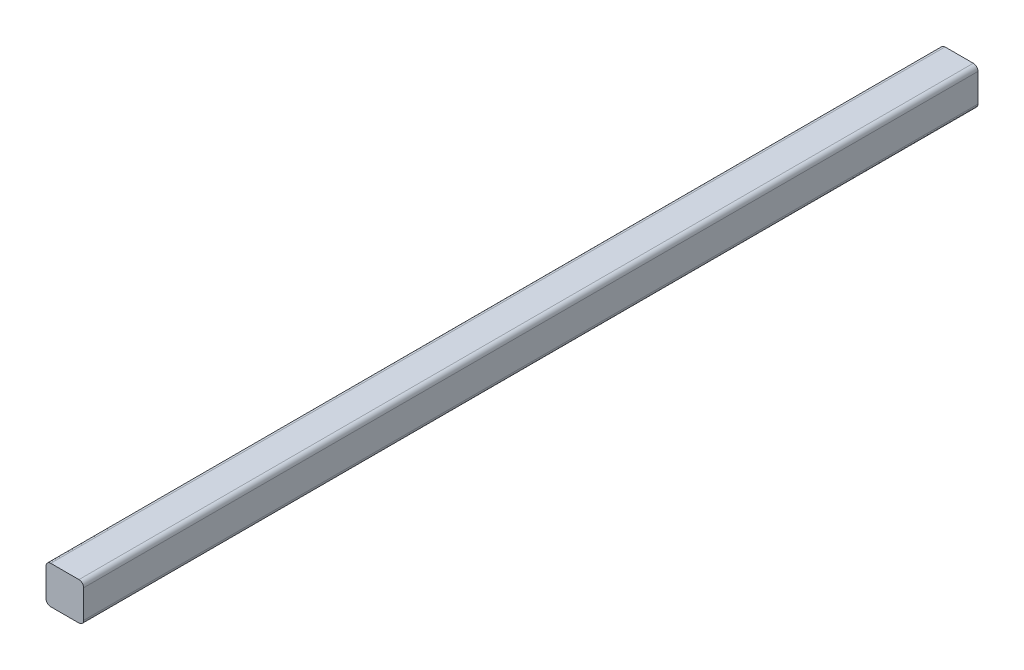
SolidWorks part; units mm, degrees
ref_plane "Front Plane" through (0, 0, 0) normal (0, 0, 1) x (1, 0, 0)
ref_plane "Top Plane" through (0, 0, 0) normal (0, 1, 0) x (1, 0, 0)
ref_plane "Right Plane" through (0, 0, 0) normal (1, 0, 0) x (0, 0, -1)
sketch "Sketch2" plane through (0, 0, 0) normal (0, 0, 1) x (1, 0, 0)
  circle A0 centre (0, 0) radius 1.25
  dimension "D1" = 2.5
sketch "Sketch3" plane through (0, 0, 0) normal (0, 0, 1) x (1, 0, 0)
  line L5 (-2, 2) -> (2, 2)
  line L6 (-2, 2) -> (-2, -2)
  line L7 (-2, -2) -> (2, -2)
  line L8 (2, 2) -> (2, -2)
  point P4 (0, 2)
  point P6 (-2, 0)
  dimension "D1" = 4
extrude "Boss-Extrude1" add sketch "Sketch3" along normal blind 95
fillet "Fillet1" radius 0.5 4 edges at (2, 2, 47.5) (2, -2, 47.5) (-2, -2, 47.5) (-2, 2, 47.5)
equation "\"length\"=95"
equation "\"D1@Boss-Extrude1\"=\"length\""
